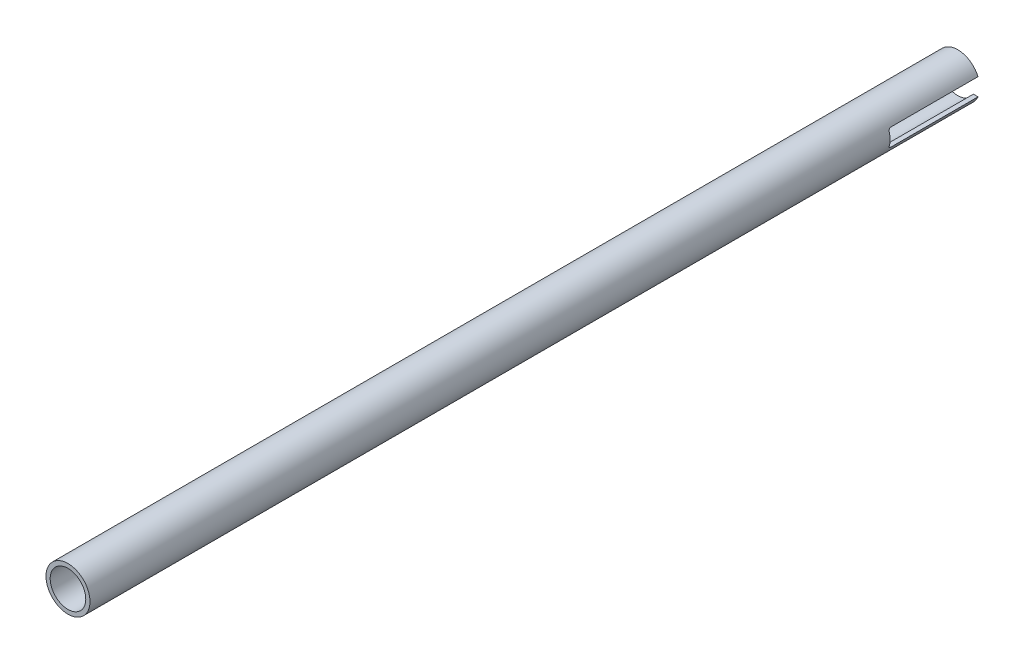
SolidWorks part; units mm, degrees
material "AISI 4130 Steel, annealed at 865C"
ref_plane "Front Plane" through (0, 0, 0) normal (0, 0, 1) x (1, 0, 0)
ref_plane "Top Plane" through (0, 0, 0) normal (0, 1, 0) x (1, 0, 0)
ref_plane "Right Plane" through (0, 0, 0) normal (1, 0, 0) x (0, 0, -1)
sketch "Sketch1" plane through (0, 0, 0) normal (0, 0, 1) x (1, 0, 0)
  circle A0 centre (0, 0) radius 6.477
  circle A1 centre (0, 0) radius 8.001
  dimension "D1" = 12.954
  dimension "D2" = 16.002
extrude "Boss-Extrude1" add sketch "Sketch1" along normal blind 323.85
sketch "Sketch2" plane through (0, 0, 0) normal (1, 0, 0) x (0, 0, -1)
  line L0 (0, 3.175) -> (-31.75, 3.175)
  line L1 (0, 8.8011) -> (0, -8.8011) construction
  line L2 (-31.75, -3.175) -> (0, -3.175)
  line L3 (-32.639, 2.286) -> (-32.639, -2.286)
  line L4 (0, -8.001) -> (0, 8.001) construction
  arc A0 (-32.639, 2.286) -> (-31.75, 3.175) centre (-31.75, 2.286) cw
  arc A1 (-31.75, -3.175) -> (-32.639, -2.286) centre (-31.75, -2.286) cw
  point P2 (-25.4, -0.889)
  point P7 (0, 0)
  point P11 (0, 0)
  point P12 (-27.4684, -1.1066)
  point P13 (-27.4684, 1.0971)
  dimension "D5" = 31.75
  dimension "D1" = 4.572
  dimension "D2" = 31.75
  dimension "D3" = 6.35
  dimension "D4" = 3.175
extrude "Cut-Extrude2" cut sketch "Sketch2" against normal through all both and the other way through all
